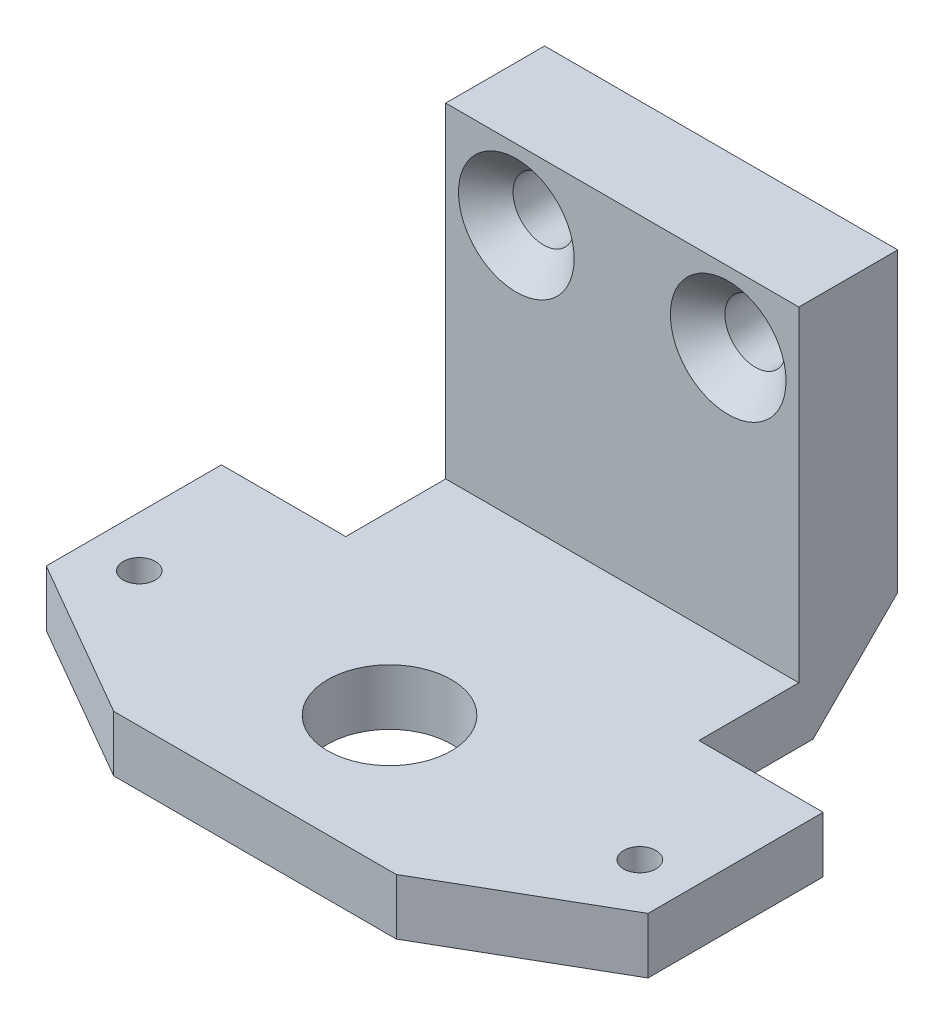
SolidWorks part; units mm, degrees
material "6061 Alloy"
ref_plane "Front Plane" through (0, 0, 0) normal (0, 0, 1) x (1, 0, 0)
ref_plane "Top Plane" through (0, 0, 0) normal (0, 1, 0) x (1, 0, 0)
ref_plane "Right Plane" through (0, 0, 0) normal (1, 0, 0) x (0, 0, -1)
sketch "Sketch1" plane through (0, 0, 0) normal (0, 1, 0) x (1, 0, 0)
  line L0 (-27.051, 7.874) -> (-15.875, 7.874)
  line L1 (27.051, 7.874) -> (27.051, -7.874)
  line L2 (27.051, -7.874) -> (12.7, -16.1596)
  line L3 (12.7, -16.1596) -> (-12.7, -16.1596)
  line L4 (-12.7, -16.1596) -> (-27.051, -7.874)
  line L5 (-27.051, -7.874) -> (-27.051, 7.874)
  line L6 (-15.875, 7.874) -> (-15.875, 16.8604)
  line L7 (-15.875, 16.8604) -> (15.875, 16.8604)
  line L8 (15.875, 16.8604) -> (15.875, 7.874)
  line L9 (15.875, 7.874) -> (27.051, 7.874)
  line L10 (0, -55) -> (0, 55) construction
  line L11 (-27.051, 0) -> (27.051, 0) construction
  line L14 (-55, 0) -> (55, 0) construction
  point P2 (0, -16.1596)
  point P13 (0, 16.8604)
  point P14 (0, 0)
  dimension "D1" = 25.4
  dimension "D3" = 54.102
  dimension "D4" = 31.75
  dimension "D5" = 33.02
  dimension "D2" = 15.748
  dimension "D6" = 30
extrude "Boss-Extrude1" add sketch "Sketch1" along normal blind 5.0292 contours L0 L6 L7 L8 L9 L1 L2 L3 L4 L5
sketch "Sketch2" plane through (0, 0, 0) normal (0, 1, 0) x (1, 0, 0)
  line L0 (0, -55) -> (0, 55) construction
  line L1 (15.875, 25.7504) -> (-15.875, 25.7504)
  line L2 (15.875, 25.7504) -> (15.875, 16.8604)
  line L3 (15.875, 16.8604) -> (-15.875, 16.8604)
  line L4 (-15.875, 25.7504) -> (-15.875, 16.8604)
  line L5 (15.875, 25.7504) -> (-15.875, 16.8604) construction
  line L6 (15.875, 16.8604) -> (-15.875, 25.7504) construction
  point P0 (0, 21.3054)
  dimension "D1" = 8.89
extrude "Boss-Extrude2" add sketch "Sketch2" along normal blind 34.29
sketch "Sketch3" plane through (15.875, 0, 0) normal (1, 0, 0) x (0, 0, -1)
  line L0 (25.7504, 34.29) -> (25.7504, 0) construction
  line L2 (18.161, 0) -> (-18.161, 0) construction
  line L3 (25.7504, 7.62) -> (18.1304, 0)
  line L4 (25.7504, 0) -> (7.874, 0) construction
  point P0 (25.7504, 7.62)
  point P5 (18.1304, 0)
  dimension "D2" = 7.62
  dimension "D1" = 7.62
extrude "Cut-Extrude1" cut sketch "Sketch3" against normal through all and the other way through all
sketch "Sketch4" plane through (0, 0, -16.8604) normal (0, 0, 1) x (1, 0, 0)
  line L0 (-9.525, 27.94) -> (9.525, 27.94)
  line L1 (0, -18.8595) -> (0, 18.8595) construction
  point P0 (-9.525, 27.94)
  point P1 (9.525, 27.94)
  point P2 (0, 27.94)
  point P7 (0, 0)
  point P10 (0, 0)
  dimension "D1" = 19.05
hole_wizard "CSK for M5 Flat Head Machine Screw1" positions "Sketch5" profile "Sketch6" countersink size "M5" standard "ANSI Metric" end condition through all
sketch "Sketch5" plane through (0, 0, -16.8604) normal (0, 0, 1) x (1, 0, 0)
  point P0 (-9.525, 27.94)
  point P3 (9.525, 27.94)
sketch "Sketch6" plane through (-9.525, 27.94, -16.8604) normal (1, 0, 0) x (0, -1, 0)
  line L0 (0, 0) -> (0, 8.89)
  line L1 (0, 8.89) -> (2.75, 8.89)
  line L2 (2.75, 8.89) -> (2.75, 2.45)
  line L3 (2.75, 2.45) -> (5.2, 0)
  line L5 (5.2, 0) -> (0, 0)
  line L6 (-2.75, 2.45) -> (-5.2, 0) construction
  line L11 (0, -6.35) -> (0, 107.95) construction
  dimension "Thru Hole Dia." = 5.5
  dimension "Thru Hole Depth" = 8.89
  dimension "Near C'Sink Dia." = 10.4
  dimension "Near C'Sink Angle" = 90
sketch "Sketch7" plane through (0, 5.0292, 0) normal (0, 1, 0) x (1, 0, 0)
  line L0 (0, -18.8595) -> (0, 18.8595) construction
  line L1 (-27.051, -7.874) -> (-27.051, 7.874) construction
  circle A0 centre (0, -4.064) radius 5.5562
  point P0 (0, -4.064)
  point P5 (-27.051, -4.064)
  dimension "D1" = 11.1125
  dimension "D2" = 3.81
extrude "Cut-Extrude2" cut sketch "Sketch7" against normal through all contours A0
sketch "Sketch8" plane through (0, 5.0292, 0) normal (0, 1, 0) x (1, 0, 0)
  line L2 (22.5, -4.064) -> (-22.5, -4.064) construction
  line L3 (0, -18.8595) -> (0, 18.8595) construction
  circle A0 centre (0, -4.064) radius 5.5563 construction
  point P6 (0, -4.064)
  dimension "D1" = 3.81
  dimension "D2" = 45
sketch "Sketch11" [suppressed] plane through (0, 5.0292, 0) normal (0, 1, 0) x (1, 0, 0)
  line L0 (17.018, 16.8604) -> (17.018, 7.874) construction
  line L1 (-27.051, 7.874) -> (-17.018, 7.874)
  line L2 (-27.051, 7.874) -> (-27.051, -16.1596)
  line L3 (-27.051, -16.1596) -> (-17.018, -16.1596)
  line L4 (-17.018, 7.874) -> (-17.018, -16.1596)
  line L5 (27.051, 7.874) -> (17.018, 7.874)
  line L6 (27.051, 7.874) -> (27.051, -16.1596)
  line L7 (27.051, -16.1596) -> (17.018, -16.1596)
  line L8 (17.018, 7.874) -> (17.018, -16.1596)
  line L9 (-17.018, 7.874) -> (-17.018, 16.8604) construction
  line L10 (12.7, -16.1596) -> (-12.7, -16.1596) construction
extrude "Cut-Extrude3" [suppressed] cut sketch "Sketch11" against normal through all
hole_wizard "M2.5 Clearance Hole1" positions "Sketch12" profile "Sketch13" hole size "M2.5" standard "ANSI Metric" end condition up to next
sketch "Sketch12" plane through (0, 5.0292, 0) normal (0, 1, 0) x (1, 0, 0)
  point P0 (-22.5, -4.064)
  point P3 (22.5, -4.064)
sketch "Sketch13" plane through (-22.5, 5.0292, 4.064) normal (1, 0, 0) x (0, 0, 1)
  line L0 (0, 0) -> (0, 5.0292)
  line L1 (0, 5.0292) -> (1.45, 5.0292)
  line L2 (1.45, 5.0292) -> (1.45, 0)
  line L5 (1.45, 0) -> (0, 0)
  line L11 (0, -6.35) -> (0, 107.95) construction
  dimension "Thru Hole Dia." = 2.9
  dimension "Thru Hole Depth" = 5.0292
equation "\"angle\"= 30"
equation "\"D6@Sketch1\"=\"angle\""
equation "\"chamfer offset\"= 0.3in"
equation "\"D2@Sketch3\"=\"chamfer offset\""
equation "\"hole height\"= 0.25in"
equation "\"Large hole offset\"= 0.15in"
equation "\"D2@Sketch7\"=\"Large hole offset\""
equation "\"D1@Sketch3\"=\"chamfer offset\""
